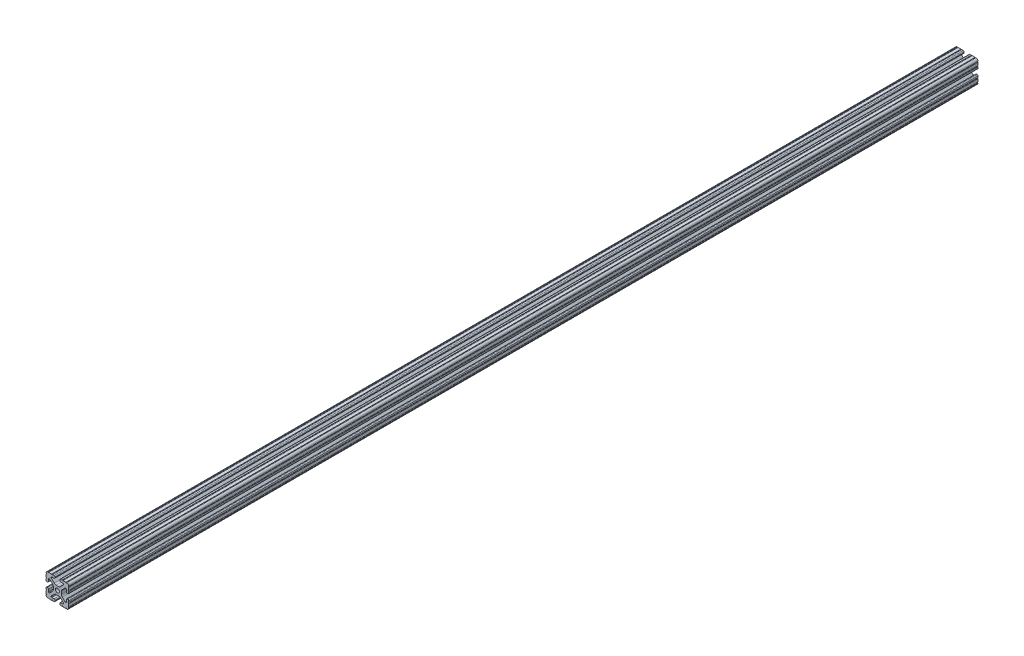
SolidWorks part; units mm, degrees
ref_plane "Front Plane" through (0, 0, 0) normal (0, 0, 1) x (1, 0, 0)
ref_plane "Top Plane" through (0, 0, 0) normal (0, 1, 0) x (1, 0, 0)
ref_plane "Right Plane" through (0, 0, 0) normal (1, 0, 0) x (0, 0, -1)
sketch "Sketch1" plane through (0, 0, 0) normal (0, 0, 1) x (1, 0, 0)
  line L0 (-10.287, 13.5524) -> (-10.287, 14.0843)
  line L1 (-9.3853, 14.986) -> (-5.6176, 14.986)
  line L2 (-4.064, 16.5396) -> (-4.064, 17.4964)
  line L3 (-5.6176, 19.05) -> (-7.9742, 19.05)
  line L4 (-9.4982, 19.05) -> (-14.3277, 19.05)
  line L5 (-19.05, 14.3277) -> (-19.05, 9.4961)
  line L6 (-19.05, 7.9763) -> (-19.05, 5.6176)
  line L7 (-17.4964, 4.064) -> (-16.5396, 4.064)
  line L8 (-14.986, 5.6176) -> (-14.986, 9.3853)
  line L9 (-14.0843, 10.287) -> (-13.516, 10.287)
  line L10 (-12.8784, 10.0229) -> (-8.1476, 5.2921)
  line L11 (-6.7564, 1.9335) -> (-6.7564, -1.9335)
  line L12 (-8.1476, -5.2921) -> (-12.8784, -10.0229)
  line L13 (-13.516, -10.287) -> (-14.0843, -10.287)
  line L14 (-14.986, -9.3853) -> (-14.986, -5.6176)
  line L15 (-16.5396, -4.064) -> (-17.4964, -4.064)
  line L16 (-19.05, -5.6176) -> (-19.05, -7.9763)
  line L17 (-19.05, -9.4961) -> (-19.05, -14.3277)
  line L18 (-14.3277, -19.05) -> (-9.4961, -19.05)
  line L19 (-7.9763, -19.05) -> (-5.6176, -19.05)
  line L20 (-4.064, -17.4964) -> (-4.064, -16.5396)
  line L21 (-5.6176, -14.986) -> (-9.3853, -14.986)
  line L22 (-10.287, -14.0843) -> (-10.287, -13.5524)
  line L23 (-10.0229, -12.9148) -> (-5.2522, -8.144)
  line L24 (-1.9022, -6.7564) -> (1.9022, -6.7564)
  line L25 (5.2522, -8.144) -> (10.0229, -12.9148)
  line L26 (10.287, -13.5524) -> (10.287, -14.0843)
  line L27 (9.3853, -14.986) -> (5.6176, -14.986)
  line L28 (4.064, -16.5396) -> (4.064, -17.4964)
  line L29 (5.6176, -19.05) -> (7.9763, -19.05)
  line L30 (9.4961, -19.05) -> (14.3277, -19.05)
  line L31 (19.05, -14.3277) -> (19.05, -9.4961)
  line L32 (19.05, -7.9763) -> (19.05, -5.6176)
  line L33 (17.4964, -4.064) -> (16.5396, -4.064)
  line L34 (14.986, -5.6176) -> (14.986, -9.3853)
  line L35 (14.0843, -10.287) -> (13.516, -10.287)
  line L36 (12.8784, -10.0229) -> (8.1476, -5.2921)
  line L37 (6.7564, -1.9335) -> (6.7564, 1.9335)
  line L38 (8.1476, 5.2921) -> (12.8784, 10.0229)
  line L39 (13.516, 10.287) -> (14.0843, 10.287)
  line L40 (14.986, 9.3853) -> (14.986, 5.6176)
  line L41 (16.5396, 4.064) -> (17.4964, 4.064)
  line L42 (19.05, 5.6176) -> (19.05, 7.9763)
  line L43 (19.05, 9.4961) -> (19.05, 14.3277)
  line L44 (14.3277, 19.05) -> (9.4982, 19.05)
  line L45 (7.9742, 19.05) -> (5.6176, 19.05)
  line L46 (4.064, 17.4964) -> (4.064, 16.5396)
  line L47 (5.6176, 14.986) -> (9.3853, 14.986)
  line L48 (10.287, 14.0843) -> (10.287, 13.5524)
  line L49 (10.0229, 12.9148) -> (5.2522, 8.144)
  line L50 (1.9022, 6.7564) -> (-1.9022, 6.7564)
  line L51 (-5.2522, 8.144) -> (-10.0229, 12.9148)
  circle A0 centre (0, 0) radius 3.3274
  arc A1 (-9.3853, 14.986) -> (-10.287, 14.0843) centre (-9.3853, 14.0843) ccw
  arc A2 (-5.6176, 14.986) -> (-4.064, 16.5396) centre (-5.6176, 16.5396) ccw
  arc A3 (-4.064, 17.4964) -> (-5.6176, 19.05) centre (-5.6176, 17.4964) ccw
  arc A4 (-9.4982, 19.05) -> (-7.9742, 19.05) centre (-8.7362, 19.05) ccw
  arc A5 (-15.8475, 19.05) -> (-14.3277, 19.05) centre (-15.0876, 18.9933) ccw
  arc A6 (-15.8475, 19.05) -> (-19.05, 15.8475) centre (-15.8751, 15.8751) ccw
  arc A7 (-19.05, 14.3277) -> (-19.05, 15.8475) centre (-18.9933, 15.0876) ccw
  arc A8 (-19.05, 7.9763) -> (-19.05, 9.4961) centre (-18.9933, 8.7362) ccw
  arc A9 (-19.05, 5.6176) -> (-17.4964, 4.064) centre (-17.4964, 5.6176) ccw
  arc A10 (-16.5396, 4.064) -> (-14.986, 5.6176) centre (-16.5396, 5.6176) ccw
  arc A11 (-14.0843, 10.287) -> (-14.986, 9.3853) centre (-14.0843, 9.3853) ccw
  arc A12 (-12.8784, 10.0229) -> (-13.516, 10.287) centre (-13.516, 9.3853) ccw
  arc A13 (-6.7564, 1.9335) -> (-8.1476, 5.2921) centre (-11.5062, 1.9335) ccw
  arc A14 (-8.1476, -5.2921) -> (-6.7564, -1.9335) centre (-11.5062, -1.9335) ccw
  arc A15 (-13.516, -10.287) -> (-12.8784, -10.0229) centre (-13.516, -9.3853) ccw
  arc A16 (-14.986, -9.3853) -> (-14.0843, -10.287) centre (-14.0843, -9.3853) ccw
  arc A17 (-14.986, -5.6176) -> (-16.5396, -4.064) centre (-16.5396, -5.6176) ccw
  arc A18 (-17.4964, -4.064) -> (-19.05, -5.6176) centre (-17.4964, -5.6176) ccw
  arc A19 (-19.05, -9.4961) -> (-19.05, -7.9763) centre (-18.9933, -8.7362) ccw
  arc A20 (-19.05, -15.8475) -> (-19.05, -14.3277) centre (-18.9933, -15.0876) ccw
  arc A21 (-19.05, -15.8475) -> (-15.8475, -19.05) centre (-15.8751, -15.8751) ccw
  arc A22 (-14.3277, -19.05) -> (-15.8475, -19.05) centre (-15.0876, -18.9933) ccw
  arc A23 (-7.9763, -19.05) -> (-9.4961, -19.05) centre (-8.7362, -18.9933) ccw
  arc A24 (-5.6176, -19.05) -> (-4.064, -17.4964) centre (-5.6176, -17.4964) ccw
  arc A25 (-4.064, -16.5396) -> (-5.6176, -14.986) centre (-5.6176, -16.5396) ccw
  arc A26 (-10.287, -14.0843) -> (-9.3853, -14.986) centre (-9.3853, -14.0843) ccw
  arc A27 (-10.0229, -12.9148) -> (-10.287, -13.5524) centre (-9.3853, -13.5524) ccw
  arc A28 (-1.9022, -6.7564) -> (-5.2522, -8.144) centre (-1.9022, -11.494) ccw
  arc A29 (5.2522, -8.144) -> (1.9022, -6.7564) centre (1.9022, -11.494) ccw
  arc A30 (10.287, -13.5524) -> (10.0229, -12.9148) centre (9.3853, -13.5524) ccw
  arc A31 (9.3853, -14.986) -> (10.287, -14.0843) centre (9.3853, -14.0843) ccw
  arc A32 (5.6176, -14.986) -> (4.064, -16.5396) centre (5.6176, -16.5396) ccw
  arc A33 (4.064, -17.4964) -> (5.6176, -19.05) centre (5.6176, -17.4964) ccw
  arc A34 (9.4961, -19.05) -> (7.9763, -19.05) centre (8.7362, -18.9933) ccw
  arc A35 (15.8475, -19.05) -> (14.3277, -19.05) centre (15.0876, -18.9933) ccw
  arc A36 (15.8475, -19.05) -> (19.05, -15.8475) centre (15.8751, -15.8751) ccw
  arc A37 (19.05, -14.3277) -> (19.05, -15.8475) centre (18.9933, -15.0876) ccw
  arc A38 (19.05, -7.9763) -> (19.05, -9.4961) centre (18.9933, -8.7362) ccw
  arc A39 (19.05, -5.6176) -> (17.4964, -4.064) centre (17.4964, -5.6176) ccw
  arc A40 (16.5396, -4.064) -> (14.986, -5.6176) centre (16.5396, -5.6176) ccw
  arc A41 (14.0843, -10.287) -> (14.986, -9.3853) centre (14.0843, -9.3853) ccw
  arc A42 (12.8784, -10.0229) -> (13.516, -10.287) centre (13.516, -9.3853) ccw
  arc A43 (6.7564, -1.9335) -> (8.1476, -5.2921) centre (11.5062, -1.9335) ccw
  arc A44 (8.1476, 5.2921) -> (6.7564, 1.9335) centre (11.5062, 1.9335) ccw
  arc A45 (13.516, 10.287) -> (12.8784, 10.0229) centre (13.516, 9.3853) ccw
  arc A46 (14.986, 9.3853) -> (14.0843, 10.287) centre (14.0843, 9.3853) ccw
  arc A47 (14.986, 5.6176) -> (16.5396, 4.064) centre (16.5396, 5.6176) ccw
  arc A48 (17.4964, 4.064) -> (19.05, 5.6176) centre (17.4964, 5.6176) ccw
  arc A49 (19.05, 9.4961) -> (19.05, 7.9763) centre (18.9933, 8.7362) ccw
  arc A50 (19.05, 15.8475) -> (19.05, 14.3277) centre (18.9933, 15.0876) ccw
  arc A51 (19.05, 15.8475) -> (15.8475, 19.05) centre (15.8751, 15.8751) ccw
  arc A52 (14.3277, 19.05) -> (15.8475, 19.05) centre (15.0876, 18.9933) ccw
  arc A53 (7.9742, 19.05) -> (9.4982, 19.05) centre (8.7362, 19.05) ccw
  arc A54 (5.6176, 19.05) -> (4.064, 17.4964) centre (5.6176, 17.4964) ccw
  arc A55 (4.064, 16.5396) -> (5.6176, 14.986) centre (5.6176, 16.5396) ccw
  arc A56 (10.287, 14.0843) -> (9.3853, 14.986) centre (9.3853, 14.0843) ccw
  arc A57 (10.0229, 12.9148) -> (10.287, 13.5524) centre (9.3853, 13.5524) ccw
  arc A58 (1.9022, 6.7564) -> (5.2522, 8.144) centre (1.9022, 11.494) ccw
  arc A59 (-5.2522, 8.144) -> (-1.9022, 6.7564) centre (-1.9022, 11.494) ccw
  arc A60 (-10.287, 13.5524) -> (-10.0229, 12.9148) centre (-9.3853, 13.5524) ccw
extrude "Boss-Extrude1" add sketch "Sketch1" along normal mid plane 1524
